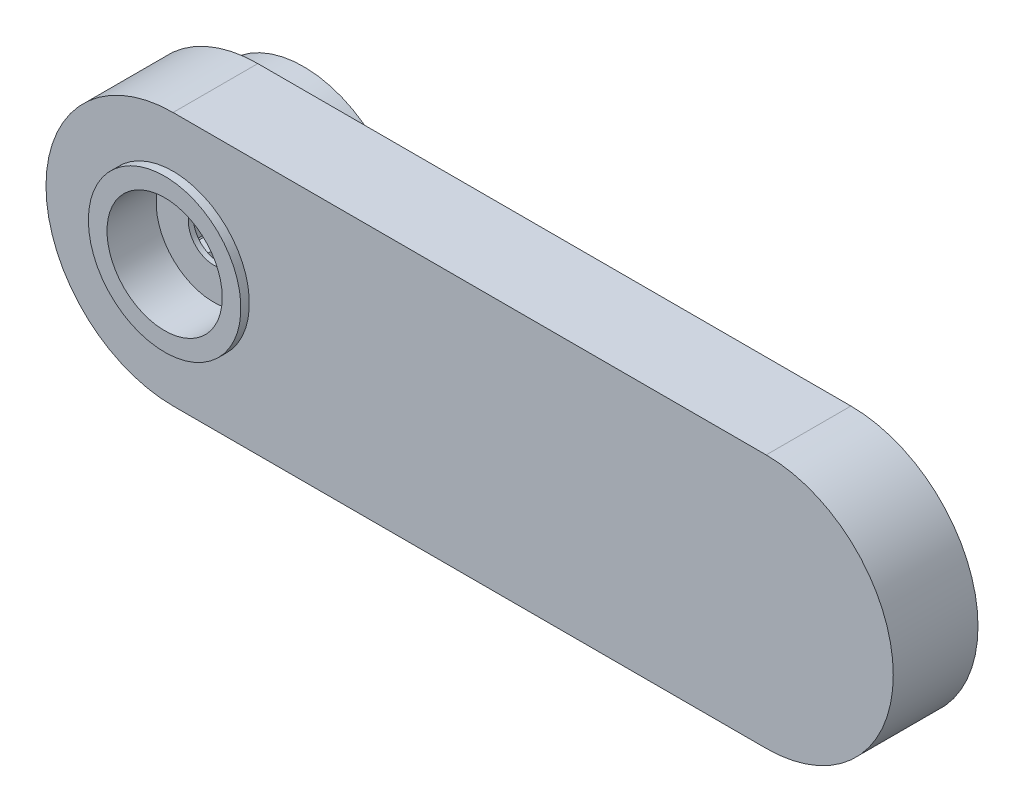
SolidWorks part; units mm, degrees
ref_plane "Front" through (0, 0, 0) normal (0, 0, 1) x (1, 0, 0)
ref_plane "Top" through (0, 0, 0) normal (0, 1, 0) x (1, 0, 0)
ref_plane "Right" through (0, 0, 0) normal (1, 0, 0) x (0, 0, -1)
ref_plane "평면1" through (0, 0, 0) normal (0, 0, -1) x (-1, 0, 0)
sketch "스케치1" plane through (0, 0, 0) normal (0, 0, -1) x (-1, 0, 0)
  line L1 (0, 0) -> (-35, 0) construction
  line L3 (0, -7.5) -> (-35, -7.5)
  line L4 (0, 7.5) -> (-35, 7.5)
  arc A3 (0, -7.5) -> (0, 7.5) centre (0, 0) ccw
  arc A4 (-35, 7.5) -> (-35, -7.5) centre (-35, 0) ccw
  point P2 (-17.5, 0)
  point P7 (7.5, 0)
  point P10 (-42.5, 0)
  dimension "D1" = 7.5
  dimension "D2" = 50
extrude "보스-돌출1" add sketch "스케치1" against normal blind 5
sketch "스케치2" plane through (0, 0, 0) normal (0, 0, -1) x (-1, 0, 0)
  circle A0 centre (0, 0) radius 6
extrude "보스-돌출2" add sketch "스케치2" along normal blind 2.7
sketch "스케치3" plane through (0, 0, -2.7) normal (0, 0, -1) x (-1, 0, 0)
  line L0 (-0.8205, 3.6591) -> (-1.3219, 2.969)
  line L1 (-1.3219, 2.969) -> (-2.1702, 3.0582)
  line L2 (-2.2379, 3.0091) -> (-2.4152, 2.1747)
  line L3 (-2.4152, 2.1747) -> (-3.2265, 1.9111)
  line L4 (-3.2683, 1.8387) -> (-3.0909, 1.0043)
  line L5 (-3.0909, 1.0043) -> (-3.7249, 0.4335)
  line L6 (-3.7336, 0.3504) -> (-3.2322, -0.3397)
  line L7 (-3.2322, -0.3397) -> (-3.5792, -1.119)
  line L8 (-3.5533, -1.1985) -> (-2.8146, -1.625)
  line L9 (-2.8146, -1.625) -> (-2.8146, -2.478)
  line L10 (-2.7587, -2.5401) -> (-1.9103, -2.6293)
  line L11 (-1.9103, -2.6293) -> (-1.5633, -3.4086)
  line L12 (-1.487, -3.4426) -> (-0.6757, -3.179)
  line L13 (-0.6757, -3.179) -> (-0.0418, -3.7498)
  line L14 (0.0418, -3.7498) -> (0.6757, -3.179)
  line L15 (0.6757, -3.179) -> (1.487, -3.4426)
  line L16 (1.5633, -3.4086) -> (1.9103, -2.6293)
  line L17 (1.9103, -2.6293) -> (2.7587, -2.5401)
  line L18 (2.8146, -2.478) -> (2.8146, -1.625)
  line L19 (2.8146, -1.625) -> (3.5533, -1.1985)
  line L20 (3.5792, -1.119) -> (3.2322, -0.3397)
  line L21 (3.2322, -0.3397) -> (3.7336, 0.3504)
  line L22 (3.7249, 0.4335) -> (3.0909, 1.0043)
  line L23 (3.0909, 1.0043) -> (3.2683, 1.8387)
  line L24 (3.2265, 1.9111) -> (2.4152, 2.1747)
  line L25 (2.4152, 2.1747) -> (2.2379, 3.0091)
  line L26 (2.1702, 3.0582) -> (1.3219, 2.969)
  line L27 (1.3219, 2.969) -> (0.8205, 3.6591)
  line L28 (0.7387, 3.6765) -> (0, 3.25)
  line L29 (0, 3.25) -> (-0.7387, 3.6765)
  arc A0 (-0.7387, 3.6765) -> (-0.8205, 3.6591) centre (0, 0) ccw
  arc A1 (-2.1702, 3.0582) -> (-2.2379, 3.0091) centre (0, 0) ccw
  arc A2 (-3.2265, 1.9111) -> (-3.2683, 1.8387) centre (0, 0) ccw
  arc A3 (-3.7249, 0.4335) -> (-3.7336, 0.3504) centre (0, 0) ccw
  arc A4 (-3.5792, -1.119) -> (-3.5533, -1.1985) centre (0, 0) ccw
  arc A5 (-2.8146, -2.478) -> (-2.7587, -2.5401) centre (0, 0) ccw
  arc A6 (-1.5633, -3.4086) -> (-1.487, -3.4426) centre (0, 0) ccw
  arc A7 (-0.0418, -3.7498) -> (0.0418, -3.7498) centre (0, 0) ccw
  arc A8 (1.487, -3.4426) -> (1.5633, -3.4086) centre (0, 0) ccw
  arc A9 (2.7587, -2.5401) -> (2.8146, -2.478) centre (0, 0) ccw
  arc A10 (3.5533, -1.1985) -> (3.5792, -1.119) centre (0, 0) ccw
  arc A11 (3.7336, 0.3504) -> (3.7249, 0.4335) centre (0, 0) ccw
  arc A12 (3.2683, 1.8387) -> (3.2265, 1.9111) centre (0, 0) ccw
  arc A13 (2.2379, 3.0091) -> (2.1702, 3.0582) centre (0, 0) ccw
  arc A14 (0.8205, 3.6591) -> (0.7387, 3.6765) centre (0, 0) ccw
extrude "컷-돌출1" cut sketch "스케치3" against normal blind 5
ref_plane "평면2" through (0, 0, 0) normal (0, -1, 0) x (1, 0, 0)
sketch "스케치4" plane through (0, 0, 0) normal (0, -1, 0) x (1, 0, 0)
  line L0 (4.5, 5.5) -> (0, 5.5)
  line L1 (0, 5.5) -> (0, 5)
  line L2 (0, 5) -> (4.5, 5)
  line L3 (4.5, 5) -> (4.5, 5.5)
  line L4 (0, 5.5) -> (0, 5) construction
revolve "회전1" add sketch "스케치4" angle 360 about L4
hole_wizard "M2.5 육각 머리 작은 나사용 카운터보어1" positions "스케치6" profile "스케치5" counterbore size "M2.5" standard "Ansi Metric"
sketch "스케치6" plane through (0, 0, 5.5) normal (0, 0, 1) x (1, 0, 0)
  point P0 (0, 0)
sketch "스케치5" plane through (0, 0, 5.5) normal (1, 0, 0) x (0, -1, 0)
  line L0 (0, 0) -> (0, 8.2)
  line L1 (0, 8.2) -> (1.5, 8.2)
  line L3 (1.5, 8.2) -> (1.5, 2.9)
  line L4 (1.5, 2.9) -> (3.4, 2.9)
  line L5 (3.4, 2.9) -> (3.4, 0)
  line L7 (3.4, 0) -> (0, 0)
  line L11 (0, -6.35) -> (0, 107.95) construction
  dimension "관통 구멍 지름" = 3
  dimension "관통 구멍 깊이" = 8.2
  dimension "카운터보어 지름" = 6.8
  dimension "카운터보어 깊이" = 2.9
